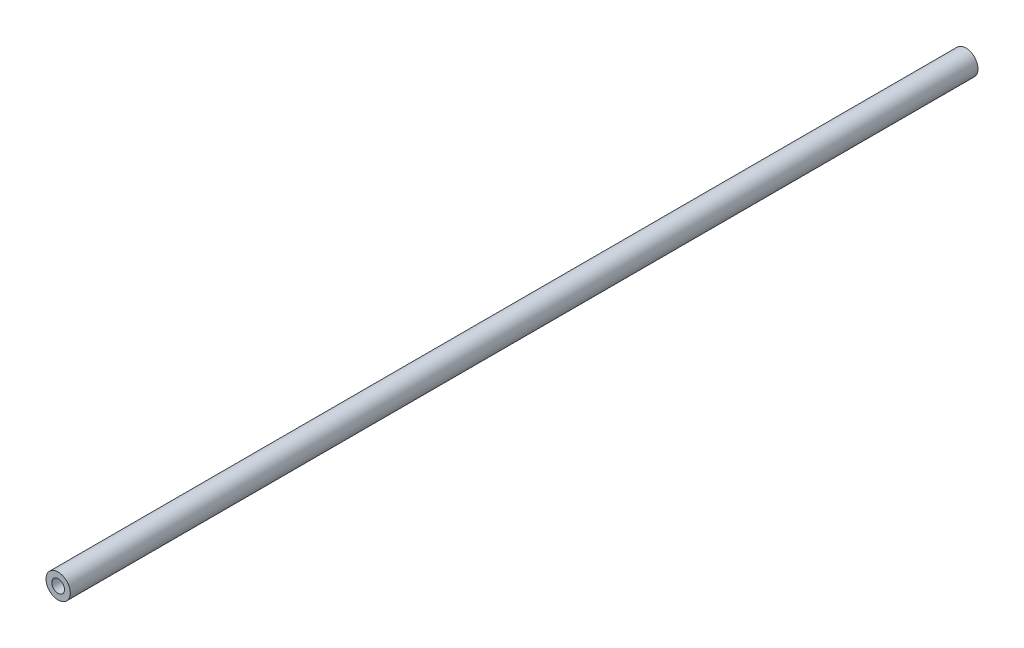
SolidWorks part; units mm, degrees
ref_plane "Front Plane" through (0, 0, 0) normal (0, 0, 1) x (1, 0, 0)
ref_plane "Top Plane" through (0, 0, 0) normal (0, 1, 0) x (1, 0, 0)
ref_plane "Right Plane" through (0, 0, 0) normal (1, 0, 0) x (0, 0, -1)
sketch "Sketch1" plane through (0, 0, 0) normal (0, 0, 1) x (1, 0, 0)
  circle A0 centre (0, 0) radius 2.4892
  circle A1 centre (0, 0) radius 4.7625
  dimension "D1" = 9.525
  dimension "D2" = 4.9784
extrude "Boss-Extrude1" add sketch "Sketch1" along normal mid plane 355.6
